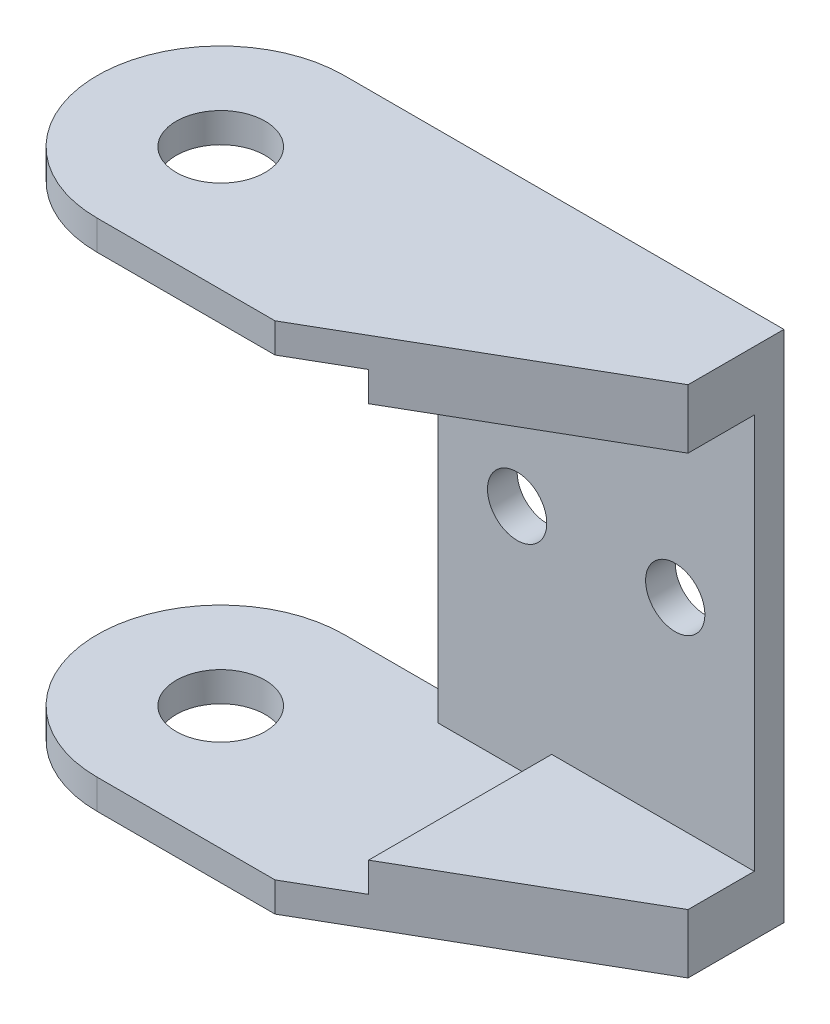
SolidWorks part; units mm, degrees
ref_plane "Front" through (0, 0, 0) normal (0, 0, 1) x (1, 0, 0)
ref_plane "Top" through (0, 0, 0) normal (0, 1, 0) x (1, 0, 0)
ref_plane "Right" through (0, 0, 0) normal (1, 0, 0) x (0, 0, -1)
sketch "Sketch1" plane through (0, 0, 0) normal (0, 0, -1) x (-1, 0, 0)
  line L0 (8, 10) -> (-8, 10)
  line L1 (-8, 10) -> (-8, -10)
  line L2 (-8, -10) -> (8, -10)
  line L3 (8, -10) -> (8, 10)
  line L4 (0, 10) -> (0, -10) construction
  dimension "D1" = 20
  dimension "D2" = 16
extrude "Boss-Extrude1" add sketch "Sketch1" against normal blind 1.5
sketch "Sketch2" plane through (0, 10, 0) normal (0, 1, 0) x (-1, 0, 0)
  line L0 (14.25, 0) -> (-8, 0)
  line L1 (-8, 0) -> (-8, 4.8501)
  line L2 (-8, 4.8501) -> (5.25, 12.5)
  line L3 (5.25, 12.5) -> (14.25, 12.5)
  line L4 (8, 0) -> (-8, 0) construction
  line L5 (-8, 1.5) -> (-8, 0) construction
  arc A0 (14.25, 12.5) -> (14.25, 0) centre (14.25, 6.25) cw
  dimension "D1" = 12.5
  dimension "D2" = 22.25
  dimension "D3" = 9
  dimension "D4" = 30
extrude "Boss-Extrude2" add sketch "Sketch2" along normal blind 3
mirror "Mirror1" about plane through (0, 0, 0) normal (0, 1, 0) of "Boss-Extrude2"
sketch "Sketch4" plane through (0, 10, 0) normal (0, 1, 0) x (1, 0, 0)
  line L0 (-20.5, -12.5) -> (-2.25, -12.5)
  line L1 (-14.25, -12.5) -> (-5.25, -12.5) construction
  line L2 (-2.25, -12.5) -> (-2.25, -1.5)
  line L3 (-2.25, -1.5) -> (-8, -1.5)
  line L4 (-8, -1.5) -> (-8, 0)
  line L5 (-8, 0) -> (-20.5, 0)
  line L6 (8, -4.8501) -> (8, -1.5) construction
  line L7 (-8, -1.5) -> (8, -1.5) construction
  line L8 (-8, -1.5) -> (-8, 0) construction
  line L9 (-8, 0) -> (-14.25, 0) construction
  line L10 (-20.5, -12.5) -> (-20.5, 0)
  arc A1 (-14.25, 0) -> (-14.25, -12.5) centre (-14.25, -6.25) ccw construction
  dimension "D1" = 10.25
extrude "Cut-Extrude1" cut sketch "Sketch4" along normal blind 1.5
mirror "Mirror2" about plane through (0, 0, 0) normal (0, 1, 0) of "Cut-Extrude1"
hole_wizard "Ø4.5 (4.5) Diameter Hole1" positions "Sketch8" profile "Sketch7" hole size "Ø4.5" standard "ANSI Metric"
sketch "Sketch8" plane through (0, 13, 0) normal (0, -1, 0) x (-1, 0, 0)
  arc A0 (14.25, -12.5) -> (14.25, 0) centre (14.25, -6.25) ccw construction
  point P0 (14.25, -6.25)
sketch "Sketch7" plane through (-14.25, 13, 6.25) normal (1, 0, 0) x (0, 0, 1)
  line L0 (0, 0) -> (0, 26)
  line L1 (0, 26) -> (2.25, 26)
  line L2 (2.25, 26) -> (2.25, 0)
  line L5 (2.25, 0) -> (0, 0)
  line L11 (0, -6.35) -> (0, 107.95) construction
  dimension "Thru Hole Dia." = 4.5
  dimension "Thru Hole Depth" = 26
mirror "Mirror3" about plane through (0, 0, 0) normal (0, 1, 0) of "Ø4.5 (4.5) Diameter Hole1"
hole_wizard "Ø3.0 (3) Diameter Hole1" positions "Sketch12" profile "Sketch11" hole size "Ø3.0" standard "ANSI Metric"
sketch "Sketch12" plane through (0, 0, 0) normal (0, 0, -1) x (-1, 0, 0)
  line L0 (-4, 0) -> (-8, 0) construction
  line L2 (-8, 10) -> (-8, -10) construction
  point P0 (-4, 0)
  point P1 (4, 0)
  dimension "D1" = 8
  dimension "D2" = 4
sketch "Sketch11" plane through (4, 0, 0) normal (1, 0, 0) x (0, 1, 0)
  line L0 (0, 0) -> (0, 12.5)
  line L1 (0, 12.5) -> (1.5, 12.5)
  line L2 (1.5, 12.5) -> (1.5, 0)
  line L5 (1.5, 0) -> (0, 0)
  line L11 (0, -6.35) -> (0, 107.95) construction
  dimension "Thru Hole Dia." = 3
  dimension "Thru Hole Depth" = 12.5
